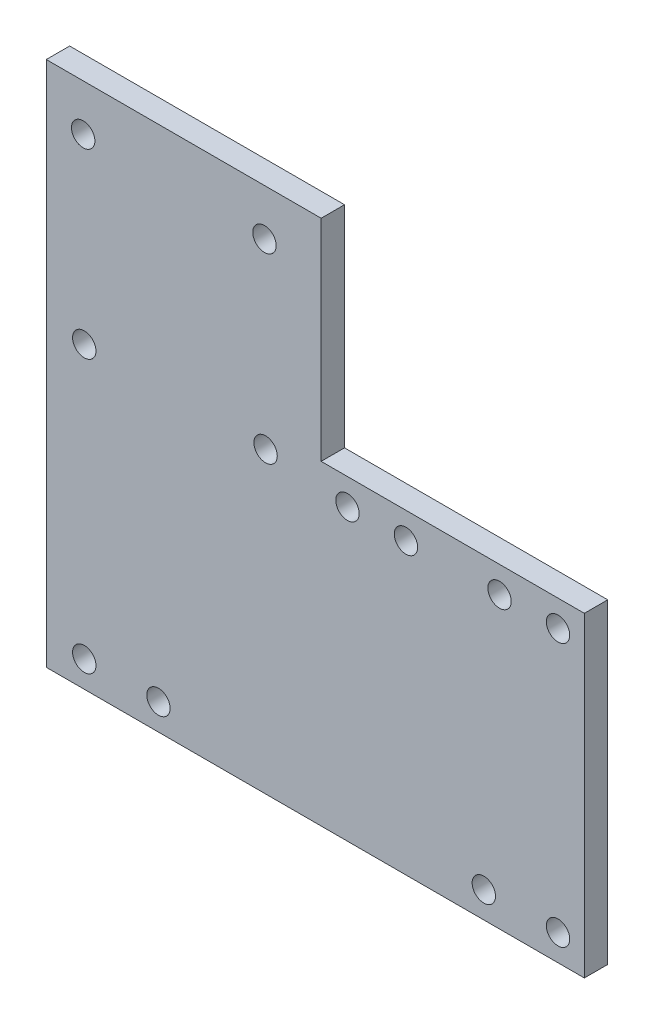
SolidWorks part; units mm, degrees
ref_plane "Front Plane" through (0, 0, 0) normal (0, 0, 1) x (1, 0, 0)
ref_plane "Top Plane" through (0, 0, 0) normal (0, 1, 0) x (1, 0, 0)
ref_plane "Right Plane" through (0, 0, 0) normal (1, 0, 0) x (0, 0, -1)
sketch "Sketch1" plane through (0, 0, 0) normal (0, 0, 1) x (1, 0, 0)
  line L0 (-45, 27) -> (-45, 63)
  line L1 (-45, -27) -> (45, -27)
  line L2 (-45, -27) -> (-45, 27)
  line L3 (0, 27) -> (45, 27)
  line L4 (45, -27) -> (45, 27)
  line L5 (-45, -27) -> (45, 27) construction
  line L6 (-45, 27) -> (45, -27) construction
  line L7 (-45, 63) -> (0, 63)
  line L8 (0, 63) -> (0, 27)
  point P0 (0, 0)
  dimension "D1" = 54
  dimension "D2" = 90
  dimension "D3" = 36
  dimension "D4" = 45
extrude "Boss-Extrude1" add sketch "Sketch1" along normal blind 4
sketch "Sketch2" plane through (0, 0, 4) normal (0, 0, 1) x (1, 0, 0)
  line L0 (-40.5, 22.5) -> (-40.5, -22.5) construction
  line L1 (-27.8166, -22.5) -> (-40.5, -22.5) construction
  line L2 (-40.5, 22.5) -> (-30.5, 22.5) construction
  line L3 (-45, 63) -> (-45, -27) construction
  line L4 (45, 27) -> (0, 27) construction
  line L5 (-45, -27) -> (45, -27) construction
  line L6 (0, 0) -> (0, 15.5228) construction
  circle A2 centre (-40.5, -22.5) radius 2
  circle A3 centre (-27.8166, -22.5) radius 2
  circle A4 centre (27.8166, -22.5) radius 2
  circle A5 centre (40.5, -22.5) radius 2
  circle A6 centre (30.5, 22.5) radius 2
  circle A7 centre (40.5, 22.5) radius 2
  dimension "D1" = 4.5
  dimension "D2" = 4.5
  dimension "D3" = 4.5
  dimension "D5" = 10
extrude "Cut-Extrude1" cut sketch "Sketch2" against normal blind 4
sketch "Sketch3" plane through (0, 0, 4) normal (0, 0, 1) x (1, 0, 0)
  circle A0 centre (-40.5, 24.0809) radius 2
  circle A1 centre (-9.5, 24.0345) radius 2
  circle A3 centre (-40.5, -22.5) radius 2 construction
  point P4 (-38.6083, 24.0345)
  point P8 (0, 0)
  dimension "D1" = 4
  dimension "D2" = 4
  dimension "D3" = 31
  dimension "D4" = 0
extrude "Cut-Extrude2" cut sketch "Sketch3" against normal blind 4
sketch "Sketch4" plane through (0, 0, 4) normal (0, 0, 1) x (1, 0, 0)
  line L0 (-40.5, 24.0809) -> (-40.6908, 55.0809) construction
  line L1 (-40.6908, 55.0809) -> (-9.6908, 55.0809) construction
  circle A0 centre (-40.6908, 55.0809) radius 2
  circle A1 centre (-9.6908, 55.0809) radius 2
  dimension "D3" = 4
  dimension "D1" = 31
  dimension "D2" = 31
extrude "Cut-Extrude3" cut sketch "Sketch4" against normal blind 4
sketch "Sketch5" plane through (0, 0, 4) normal (0, 0, 1) x (1, 0, 0)
  line L1 (-45, 63) -> (-47, 63)
  line L2 (-45, 63) -> (-45, -27)
  line L3 (-45, -27) -> (-47, -27)
  line L4 (-47, 63) -> (-47, -27)
  dimension "D1" = 2
extrude "Boss-Extrude2" add sketch "Sketch5" against normal blind 4
sketch "Sketch6" plane through (0, 0, 4) normal (0, 0, 1) x (1, 0, 0)
  line L0 (4.5, 22.5) -> (14.5, 22.5) construction
  line L1 (14.5, 22.5) -> (30.5, 22.5) construction
  line L3 (0, 27) -> (0, 63) construction
  circle A0 centre (4.5, 22.5) radius 2
  circle A1 centre (14.5, 22.5) radius 2
  dimension "D1" = 4
  dimension "D2" = 4
  dimension "D3" = 10
  dimension "D4" = 4.5
extrude "Cut-Extrude4" cut sketch "Sketch6" against normal blind 4
